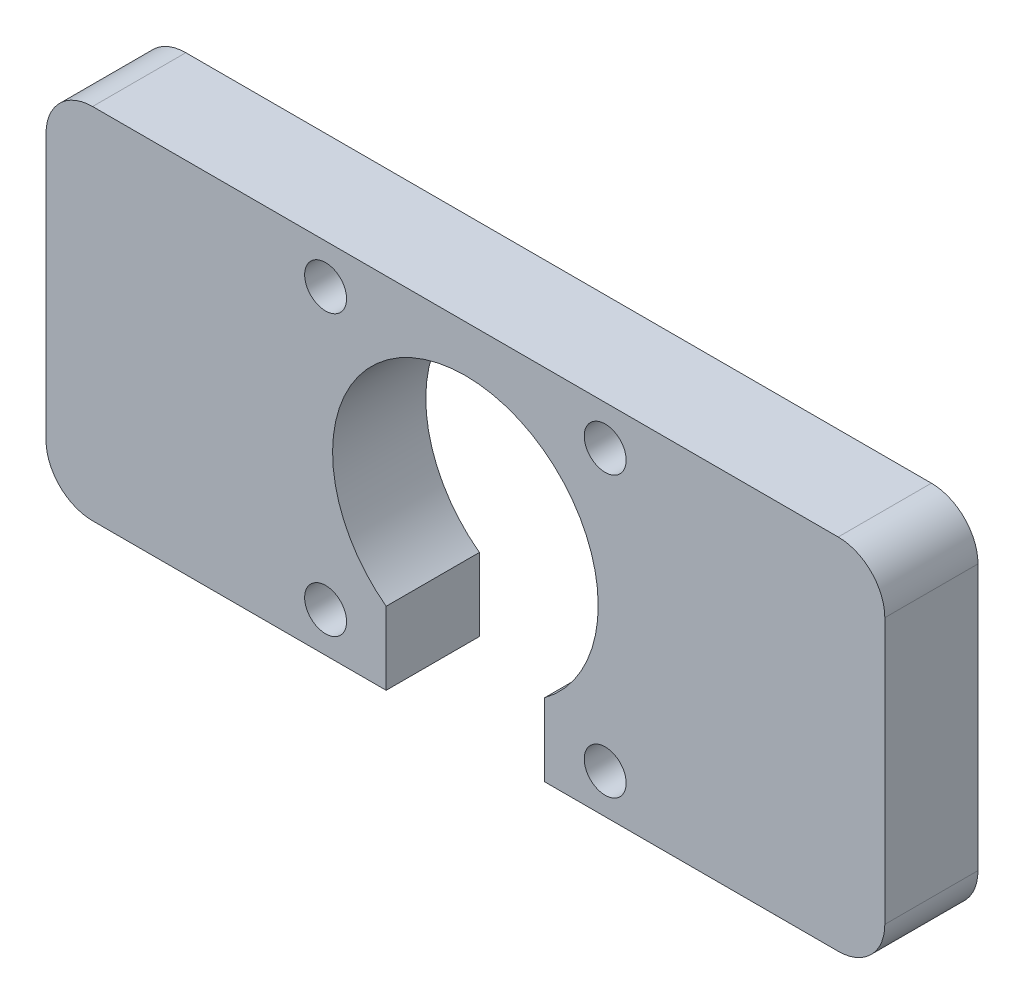
SolidWorks part; units mm, degrees
ref_plane "Front Plane" through (0, 0, 0) normal (0, 0, 1) x (1, 0, 0)
ref_plane "Top Plane" through (0, 0, 0) normal (0, 1, 0) x (1, 0, 0)
ref_plane "Right Plane" through (0, 0, 0) normal (1, 0, 0) x (0, 0, -1)
sketch "Sketch1" plane through (0, 0, 0) normal (0, 0, 1) x (1, 0, 0)
  line L0 (-15, 19.25) -> (-30, 19.25)
  line L2 (-45, 14.25) -> (-45, -14.25)
  line L4 (-15, 19.25) -> (15, 19.25)
  line L6 (15, -19.25) -> (8.5, -19.25)
  line L11 (-30, -19.25) -> (-15, -19.25)
  line L12 (-30, 19.25) -> (-40, 19.25)
  line L13 (-30, -19.25) -> (-40, -19.25)
  line L14 (-8.5, -19.25) -> (-15, -19.25)
  line L15 (0, 0) -> (0, 9.3162)
  line L16 (30, -19.25) -> (15, -19.25)
  line L17 (8.5, -16.75) -> (8.5, -11.4373)
  line L18 (-8.5, -16.75) -> (-8.5, -11.4373)
  line L19 (-8.5, -16.75) -> (-8.5, -19.25)
  line L20 (8.5, -16.75) -> (8.5, -19.25)
  line L21 (15, 19.25) -> (30, 19.25)
  line L22 (30, -19.25) -> (40, -19.25)
  line L23 (30, 19.25) -> (40, 19.25)
  line L24 (45, 14.25) -> (45, -14.25)
  arc A0 (8.5, -11.4373) -> (-8.5, -11.4373) centre (0, 0) ccw
  circle A1 centre (15, 15) radius 2.25
  circle A2 centre (-15, 15) radius 2.25
  circle A3 centre (-15, -15) radius 2.25
  circle A4 centre (15, -15) radius 2.25
  arc A19 (-40, -19.25) -> (-45, -14.25) centre (-40, -14.25) cw
  arc A20 (-40, 19.25) -> (-45, 14.25) centre (-40, 14.25) ccw
  arc A21 (40, 19.25) -> (45, 14.25) centre (40, 14.25) cw
  arc A22 (40, -19.25) -> (45, -14.25) centre (40, -14.25) ccw
  point P5 (19.25, 15)
  point P7 (-10.75, 15)
  point P13 (-10.75, -15)
  point P18 (-25.25, 0)
  point P19 (19.25, -15)
  point P20 (-15, 15)
  point P22 (15, 15)
  point P24 (15, -15)
  point P26 (-15, -15)
  point P38 (-39.75, 0)
  point P39 (-20.75, 0)
  point P51 (39.75, 0)
  dimension "D1" = 2
  dimension "D3" = 5
  dimension "D2" = 2
extrude "Boss-Extrude1" add sketch "Sketch1" along normal blind 10
